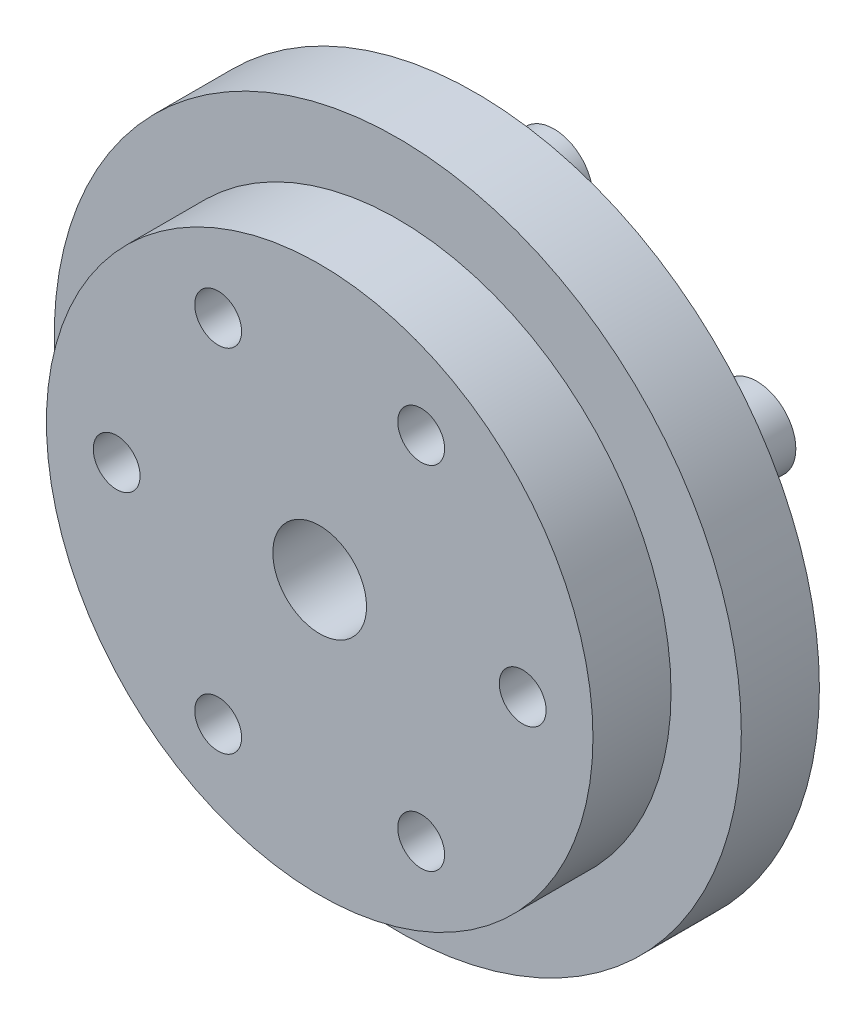
SolidWorks part; units mm, degrees
ref_plane "Front Plane" through (0, 0, 0) normal (0, 0, 1) x (1, 0, 0)
ref_plane "Top Plane" through (0, 0, 0) normal (0, 1, 0) x (1, 0, 0)
ref_plane "Right Plane" through (0, 0, 0) normal (1, 0, 0) x (0, 0, -1)
sketch "Sketch1" plane through (0, 0, 0) normal (0, 0, 1) x (1, 0, 0)
  circle A0 centre (0, 0) radius 22
  dimension "D1" = 44
extrude "Boss-Extrude1" add sketch "Sketch1" along normal blind 5
sketch "Sketch2" plane through (0, 0, 5) normal (0, 0, 1) x (1, 0, 0)
  circle A0 centre (0, 0) radius 17.5
  dimension "D1" = 35
extrude "Boss-Extrude2" add sketch "Sketch2" along normal blind 5
sketch "Sketch4" plane through (0, 0, 10) normal (0, 0, 1) x (1, 0, 0)
  circle A0 centre (0, 0) radius 8
  dimension "D1" = 16
extrude "Cut-Extrude2" cut sketch "Sketch4" against normal blind 10
sketch "Sketch5" plane through (0, 0, 10) normal (0, 0, 1) x (1, 0, 0)
  circle A0 centre (13, 0) radius 1.5
  circle A1 centre (6.5, -11.2583) radius 1.5
  circle A2 centre (-6.5, -11.2583) radius 1.5
  circle A3 centre (-13, 0) radius 1.5
  circle A4 centre (-6.5, 11.2583) radius 1.5
  circle A5 centre (6.5, 11.2583) radius 1.5
  point P15 (0, 0)
  dimension "D1" = 3
  dimension "D2" = 13
  dimension "D3" = 6
extrude "Cut-Extrude3" cut sketch "Sketch5" against normal blind 3
sketch "Sketch7" plane through (0, 0, 0) normal (0, 0, -1) x (-1, 0, 0)
  circle A0 centre (0, 15) radius 2.5
  circle A1 centre (12.9904, 7.5) radius 2.5
  circle A2 centre (12.9904, -7.5) radius 2.5
  circle A3 centre (0, -15) radius 2.5
  circle A4 centre (-12.9904, -7.5) radius 2.5
  circle A5 centre (-12.9904, 7.5) radius 2.5
  point P16 (0, 0)
  dimension "D1" = 5
  dimension "D2" = 15
  dimension "D3" = 6
extrude "Boss-Extrude4" add sketch "Sketch7" along normal blind 5
sketch "Sketch8" plane through (0, 0, 10) normal (0, 0, 1) x (1, 0, 0)
  circle A0 centre (0, 0) radius 8
  circle A1 centre (0, 0) radius 3
  dimension "D1" = 6
extrude "Boss-Extrude5" add sketch "Sketch8" against normal blind 5
